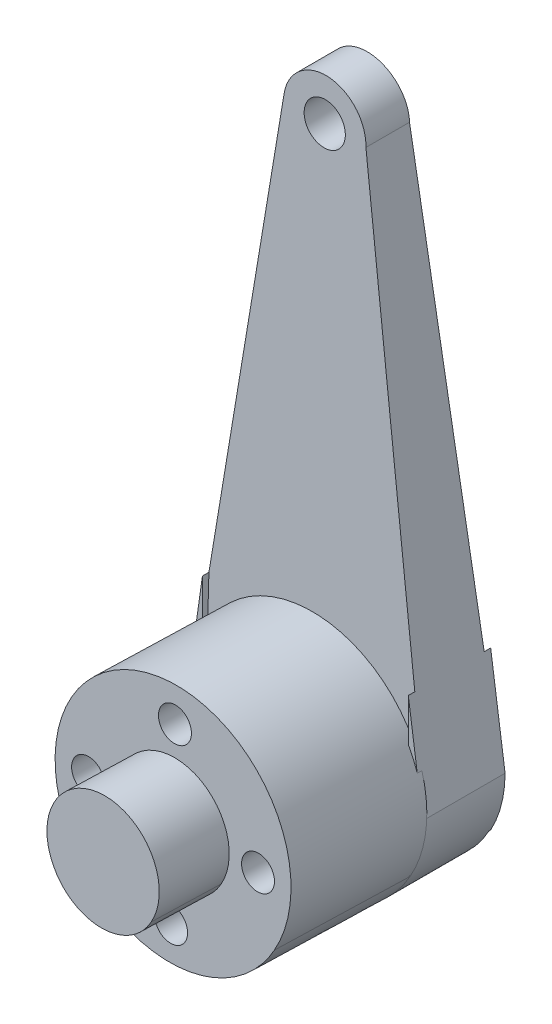
SolidWorks part; units mm, degrees
ref_plane "Front Plane" through (0, 0, 0) normal (0, 0, 1) x (1, 0, 0)
ref_plane "Top Plane" through (0, 0, 0) normal (0, 1, 0) x (1, 0, 0)
ref_plane "Right Plane" through (0, 0, 0) normal (1, 0, 0) x (0, 0, -1)
sketch "Sketch1" plane through (0, 0, 0) normal (0, 0, 1) x (1, 0, 0)
  line L0 (0, 130) -> (0, 0) construction
  line L1 (-9.9013, 131.4014) -> (-28.5, 0)
  line L2 (10, 130) -> (28.5, 0)
  arc A0 (-27.3805, 7.9094) -> (27.3686, 7.9505) centre (0, 0) ccw
  circle A1 centre (0, 0) radius 8.5
  circle A2 centre (0, 130) radius 5
  arc A3 (10, 130) -> (-9.9013, 131.4014) centre (0, 130) ccw
  dimension "D1" = 17
  dimension "D2" = 20
  dimension "D4" = 10
  dimension "D5" = 20
  dimension "D3" = 130
extrude "Boss-Extrude1" add sketch "Sketch1" along normal mid plane 20
sketch "Sketch2" plane through (0, 0, 0) normal (1, 0, 0) x (0, 0, -1)
  line L0 (-5, 140) -> (-10, -28.5)
  line L1 (10, 140) -> (-10, 140) construction
  line L2 (-10, -28.5) -> (-10, 140)
  line L3 (-10, 140) -> (-5, 140)
  dimension "D1" = 5
extrude "Cut-Extrude1" cut sketch "Sketch2" against normal mid plane 50
mirror "Mirror1" about plane through (0, 0, 0) normal (0, 0, 1) of "Cut-Extrude1"
sketch "Sketch3" plane through (0, 0.2714, 9.1462) normal (0, 0.0297, 0.9996) x (1, 0, 0)
  arc A2 (-25, -13.9615) -> (25, -13.9615) centre (0, 0) cw
  ellipse E1 centre (0, -0.2715) end of major axis (0, 28.241) minor radius 28.5 (-25, -13.9615) -> (25, -13.9615) ccw construction
  ellipse E2 centre (0, -0.2715) end of major axis (0, 28.241) minor radius 28.5 (-25, -13.9615) -> (25, -13.9615) ccw
extrude "Boss-Extrude2" add sketch "Sketch3" along normal blind 50
sketch "Sketch4" plane through (0, 1.7544, 59.1243) normal (0, 0.0297, 0.9996) x (1, 0, 0)
  circle A0 centre (0, 0) radius 5
  dimension "D1" = 10
extrude "Cut-Extrude2" cut sketch "Sketch4" against normal up to next
sketch "Sketch5" plane through (0, 0, 0) normal (0, 1, 0) x (1, 0, 0)
  line L1 (-9.5, -10) -> (9.5, -10)
  line L2 (-9.5, -10) -> (-9.5, -25)
  line L3 (-9.5, -25) -> (9.5, -25)
  line L4 (9.5, -10) -> (9.5, -25)
  ellipse E0 centre (0, -9.1543) end of major axis (-28.5, -9.1543) minor radius 0.8457 (-28.4998, -9.1514) -> (28.4998, -9.1514) ccw construction
  point P11 (0, -10)
  dimension "D1" = 19
  dimension "D2" = 15
extrude "Cut-Extrude3" cut sketch "Sketch5" against normal up to next
sketch "Sketch6" plane through (0, 1.7544, 59.1243) normal (0, 0.0297, 0.9996) x (1, 0, 0)
  arc A0 (11.8719, -6.7047) -> (-11.8719, -6.7047) centre (0, 0) ccw
  arc A1 (25, -13.9615) -> (-25, -13.9615) centre (0, 0) ccw
  arc A2 (25, -13.9615) -> (-25, -13.9615) centre (0, 0) ccw
  ellipse E1 centre (0, -0.2715) end of major axis (0, 28.241) minor radius 28.5 (-25, -13.9615) -> (25, -13.9615) ccw
  ellipse E2 centre (0, -0.2715) end of major axis (0, 28.241) minor radius 28.5 (-25, -13.9615) -> (25, -13.9615) ccw
  spline S0 degree 1 poles (-11.8719, -6.7047) (11.8719, -6.7047) knots 0 0 1 1 construction
  spline S1 degree 3 poles (-11.8719, -6.7047) (-11.2979, -7.7658) (-9.856, -9.7433) (-6.0382, -12.7827) (0, -14.4516) (6.0382, -12.7827) (9.856, -9.7433) (11.2979, -7.7658) (11.8719, -6.7047) knots 2.066792 2.066792 2.066792 2.066792 2.335492 2.604192 3.141593 3.678993 3.947693 4.216393 4.216393 4.216393 4.216393
  ellipse M4 centre (0, -0.2715) end of major axis (0, 28.241) minor radius 28.5 (-25, -13.9615) -> (25, -13.9615) ccw
  arc M5 (25, -13.9615) -> (-25, -13.9615) centre (0, 0) ccw
  dimension "D1" = 0
  dimension "D2" = 15
extrude "Cut-Extrude4" cut sketch "Sketch6" against normal blind 17 contours S1 A0 M5 M4
sketch "Sketch7" plane through (0, 1.2502, 42.1317) normal (0, 0.0297, 0.9996) x (1, 0, 0)
  line L0 (0, 0) -> (20.6343, 0) construction
  arc A0 (17.9984, -10.0912) -> (-17.9984, -10.0912) centre (0, 0) ccw construction
  arc A1 (25, -13.9615) -> (-25, -13.9615) centre (0, 0) ccw
  arc A2 (25, -13.9615) -> (-25, -13.9615) centre (0, 0) ccw construction
  circle A3 centre (20.6343, 0) radius 4
  circle A4 centre (0.1514, -20.7835) radius 4
  circle A5 centre (-20.6321, -0.3006) radius 4
  circle A6 centre (-0.1492, 20.4829) radius 4
  ellipse E1 centre (0, -0.2715) end of major axis (0, 28.241) minor radius 28.5 (-25, -13.9615) -> (25, -13.9615) ccw
  ellipse E2 centre (0, -0.2715) end of major axis (0, 28.241) minor radius 28.5 (-25, -13.9615) -> (25, -13.9615) ccw construction
  spline S0 degree 1 poles (-17.9984, -10.0912) (17.9984, -10.0912) knots 0 0 1 1 construction
  spline S1 degree 3 poles (-17.9984, -10.0912) (-17.1246, -11.6947) (-14.9342, -14.6815) (-9.4672, -19.0167) (-3.5685, -20.8266) (3.7703, -20.7722) (9.547, -18.9534) (14.9342, -14.6815) (17.1246, -11.6947) (17.9984, -10.0912) knots 2.069915 2.069915 2.069915 2.069915 2.337834 2.605754 3.082 3.215959 3.677432 3.945351 4.213271 4.213271 4.213271 4.213271 construction
  point P9 (0, 0)
  point P19 (0, 0)
  point P26 (0.0011, -0.1503)
  dimension "D3" = 8
  dimension "D1" = 0
  dimension "D2" = 8
  dimension "D4" = 4
extrude "Cut-Extrude5" cut sketch "Sketch7" against normal blind 17
sketch "Sketch8" plane through (0, 1.7544, 59.1243) normal (0, 0.0297, 0.9996) x (1, 0, 0)
  circle A0 centre (0, 0) radius 5 construction
  circle A1 centre (0, 0) radius 5
extrude "Boss-Extrude3" add sketch "Sketch8" against normal up to surface (34.2876 mm away)
